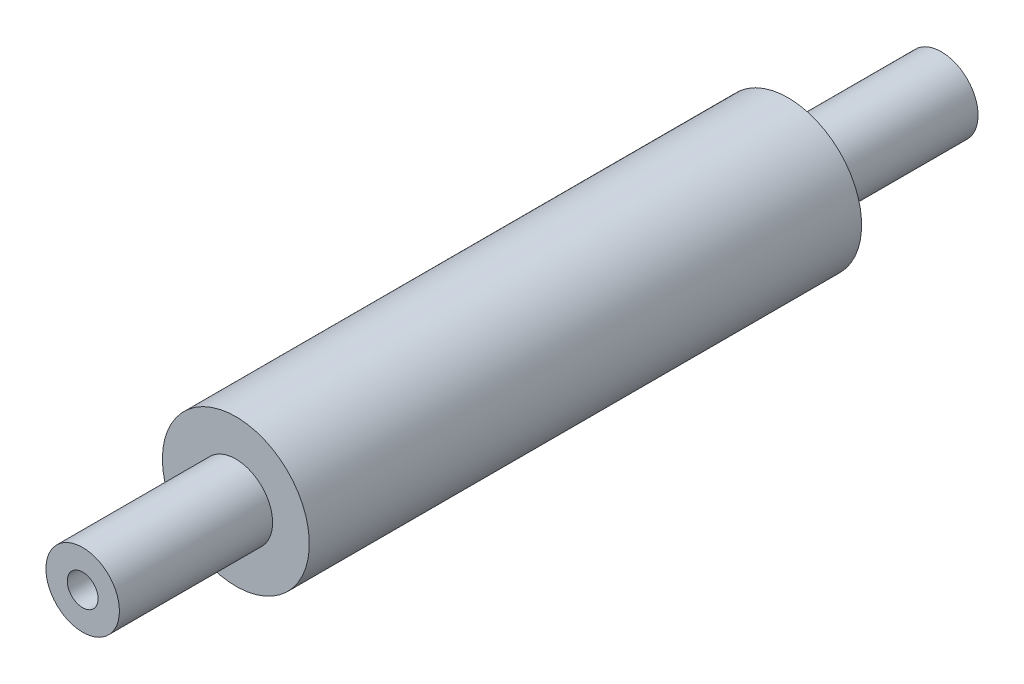
SolidWorks part; units mm, degrees
ref_plane "Alzado" through (0, 0, 0) normal (0, 0, 1) x (1, 0, 0)
ref_plane "Planta" through (0, 0, 0) normal (0, 1, 0) x (1, 0, 0)
ref_plane "Vista lateral" through (0, 0, 0) normal (1, 0, 0) x (0, 0, -1)
sketch "Croquis1" plane through (0, 0, 0) normal (0, 0, 1) x (1, 0, 0)
  circle A0 centre (0, 0) radius 9.525
  dimension "D1" = 19.05
extrude "Saliente-Extruir1" add sketch "Croquis1" along normal blind 71.6
sketch "Croquis2" plane through (0, 0, 71.6) normal (0, 0, 1) x (1, 0, 0)
  circle A0 centre (0, 0) radius 4.7625
  dimension "D1" = 9.525
extrude "Saliente-Extruir2" add sketch "Croquis2" along normal blind 19.86
sketch "Croquis3" plane through (0, 0, 0) normal (0, 0, -1) x (-1, 0, 0)
  circle A0 centre (0, 0) radius 4.7625
  dimension "D1" = 9.525
extrude "Saliente-Extruir3" add sketch "Croquis3" along normal blind 19.86
sketch "Croquis4" plane through (0, 0, -19.86) normal (0, 0, -1) x (-1, 0, 0)
  circle A0 centre (0, 0) radius 2
  dimension "D1" = 4
extrude "Cortar-Extruir1" cut sketch "Croquis4" against normal blind 5
sketch "Croquis5" plane through (0, 0, 91.46) normal (0, 0, 1) x (1, 0, 0)
  circle A0 centre (0, 0) radius 2
  dimension "D1" = 4
extrude "Cortar-Extruir2" cut sketch "Croquis5" against normal blind 5
